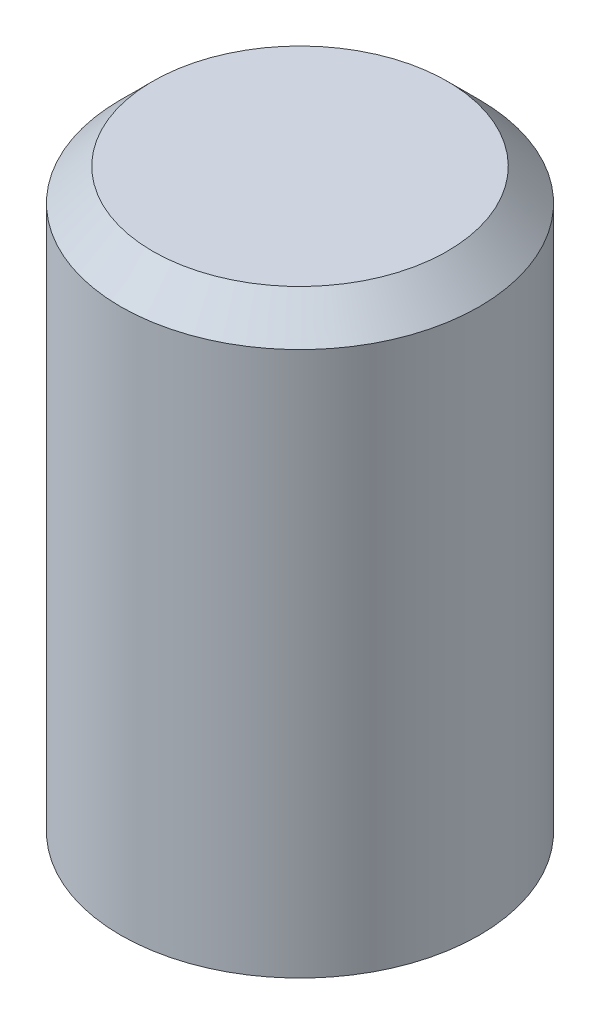
SolidWorks part; units mm, degrees
ref_plane "Front Plane" through (0, 0, 0) normal (0, 0, 1) x (1, 0, 0)
ref_plane "Top Plane" through (0, 0, 0) normal (0, 1, 0) x (1, 0, 0)
ref_plane "Right Plane" through (0, 0, 0) normal (1, 0, 0) x (0, 0, -1)
sketch "Sketch1" plane through (0, 0, 0) normal (0, 1, 0) x (1, 0, 0)
  circle A0 centre (0, 0) radius 1.4
extrude "Boss-Extrude1" add sketch "Sketch1" along normal blind 4.5
chamfer "Chamfer1" distance 0.25 angle 45 1 edges at (0, 4.5, 1.4)
